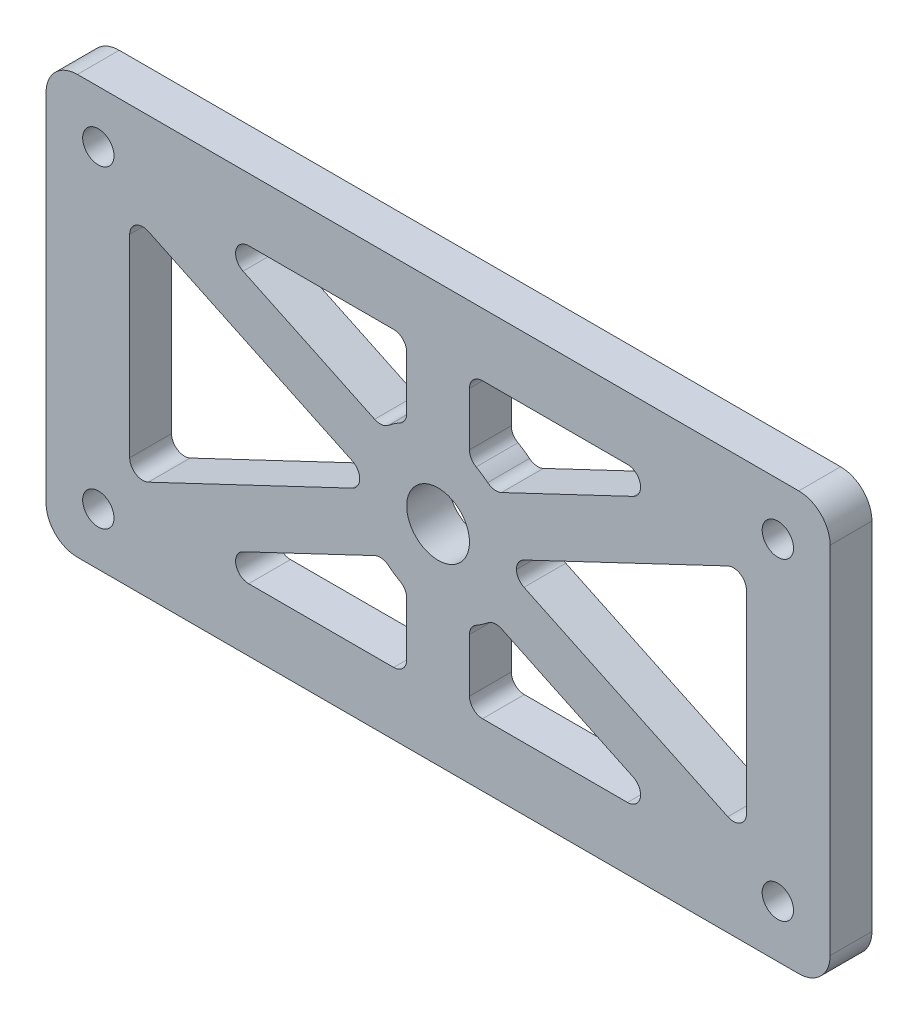
SolidWorks part; units mm, degrees
material "Thornel Mat VMA"
ref_plane "前视基准面" through (0, 0, 0) normal (0, 0, 1) x (1, 0, 0)
ref_plane "上视基准面" through (0, 0, 0) normal (0, 1, 0) x (1, 0, 0)
ref_plane "右视基准面" through (0, 0, 0) normal (1, 0, 0) x (0, 0, -1)
sketch "草图1" plane through (0, 0, 0) normal (0, 0, 1) x (1, 0, 0)
  line L1 (-37.5, -20) -> (37.5, -20)
  line L2 (-37.5, -20) -> (-37.5, 20)
  line L3 (-37.5, 20) -> (37.5, 20)
  line L4 (37.5, -20) -> (37.5, 20)
  line L5 (0, 20) -> (0, -20) construction
  line L6 (-37.5, 0) -> (37.5, 0) construction
  point P0 (0, 0)
  dimension "D1" = 75
  dimension "D2" = 40
extrude "凸台-拉伸1" add sketch "草图1" along normal blind 4
sketch "草图3" plane through (0, 0, 4) normal (0, 0, 1) x (1, 0, 0)
  circle A0 centre (0, 0) radius 3
  dimension "D1" = 6
extrude "切除-拉伸1" cut sketch "草图3" against normal blind 4
sketch "草图4" plane through (0, 0, 4) normal (0, 0, 1) x (1, 0, 0)
  line L1 (-32.5, -15) -> (32.5, -15) construction
  line L2 (-32.5, -15) -> (-32.5, 15) construction
  line L3 (-32.5, 15) -> (32.5, 15) construction
  line L4 (32.5, -15) -> (32.5, 15) construction
  line L5 (0, 15) -> (0, -15) construction
  line L6 (-32.5, 0) -> (32.5, 0) construction
  circle A0 centre (32.5, 15) radius 1.5
  circle A1 centre (-32.5, 15) radius 1.5
  circle A2 centre (-32.5, -15) radius 1.5
  circle A3 centre (32.5, -15) radius 1.5
  point P0 (0, 0)
  dimension "D3" = 3
  dimension "D1" = 30
  dimension "D2" = 65
extrude "切除-拉伸2" cut sketch "草图4" against normal blind 10
fillet "圆角1" radius 3 4 edges at (37.5, -20, 2) (37.5, 20, 2) (-37.5, -20, 2) (-37.5, 20, 2)
sketch "草图5" plane through (0, 0, 4) normal (0, 0, 1) x (1, 0, 0)
  line L0 (-29.5, 14) -> (-3, 14)
  line L1 (-3, 14) -> (-3, 6.8739)
  line L2 (-29.5, 14) -> (-29.5, -14)
  line L3 (-29.5, -14) -> (-3, -14)
  line L4 (-3, -14) -> (-3, -6.8739)
  line L5 (0, 0) -> (0, 24.5994) construction
  line L6 (34.5, 20) -> (-34.5, 20) construction
  line L7 (-34.5, -20) -> (34.5, -20) construction
  arc A0 (-3, 6.8739) -> (-3, -6.8739) centre (0, 0) ccw
  circle A1 centre (-32.5, -15) radius 1.5 construction
  dimension "D1" = 15
  dimension "D2" = 3
  dimension "D3" = 6
  dimension "D4" = 6
  dimension "D5" = 6
extrude "切除-拉伸3" cut sketch "草图5" against normal blind 10
mirror "镜向1" about plane through (0, 0, 0) normal (1, 0, 0) of "切除-拉伸3"
sketch "草图6" plane through (0, 0, 4) normal (0, 0, 1) x (1, 0, 0)
  line L0 (-29.5, 14) -> (29.5, -14) construction
  line L1 (-29.5, -14) -> (29.5, 14) construction
  line L2 (-30.5719, 11.7414) -> (28.4281, -16.2586)
  line L3 (-28.4281, -16.2586) -> (30.5719, 11.7414)
  line L4 (-28.4281, 16.2586) -> (30.5719, -11.7414)
  line L5 (-30.5719, -11.7414) -> (28.4281, 16.2586)
  line L6 (-30.5719, 11.7414) -> (-28.4281, 16.2586)
  line L7 (28.4281, -16.2586) -> (30.5719, -11.7414)
  line L8 (-28.4281, -16.2586) -> (-30.5719, -11.7414)
  line L9 (30.5719, 11.7414) -> (28.4281, 16.2586)
  circle A0 centre (0, 0) radius 7.5
  arc A1 (3, -6.8739) -> (3, 6.8739) centre (0, 0) ccw construction
  line M22 (-3, -14) -> (-29.5, -14)
  line M23 (-29.5, -14) -> (-29.5, 14)
  line M24 (-29.5, 14) -> (-3, 14)
  arc M26 (-3, 6.8739) -> (-3, -6.8739) centre (0, 0) ccw
  line M28 (29.5, 14) -> (29.5, -14)
  line M29 (29.5, -14) -> (3, -14)
  arc M31 (3, -6.8739) -> (3, 6.8739) centre (0, 0) ccw
  line M33 (3, 14) -> (29.5, 14)
  dimension "D1" = 2.5
  dimension "D2" = 2.5
extrude "凸台-拉伸2" add sketch "草图6" against normal up to surface (4 mm away) contours L5 L3 M23 M22 M26 | L4 L2 M24 M23 M26 | L5 L3 M31 M28 M33 | L4 L2 M31 M29 M28 up to face at (-12.5833, 0, 0)
fillet "圆角2" radius 1.25 24 edges at (-3, -6.8739, 2) (-3, -14, 2) (-23.669, -14, 2) (-5.3163, -5.2902, 2) (-23.669, 14, 2) (-3, 14, 2) (-3, 6.8739, 2) (-5.3163, 5.2902, 2) (-7.46, -0.7731, 2) (-29.5, -11.2328, 2) (-29.5, 11.2328, 2) (-7.46, 0.7731, 2) (3, 6.8739, 2) (3, 14, 2) (23.669, 14, 2) (5.3163, 5.2902, 2) (3, -6.8739, 2) (5.3163, -5.2902, 2) (7.46, -0.7731, 2) (7.46, 0.7731, 2) (29.5, 11.2328, 2) (29.5, -11.2328, 2) (23.669, -14, 2) (3, -14, 2)
equation "\"D4@草图5\"=\"D3@草图5\""
equation "\"D5@草图5\"=\"D3@草图5\""
